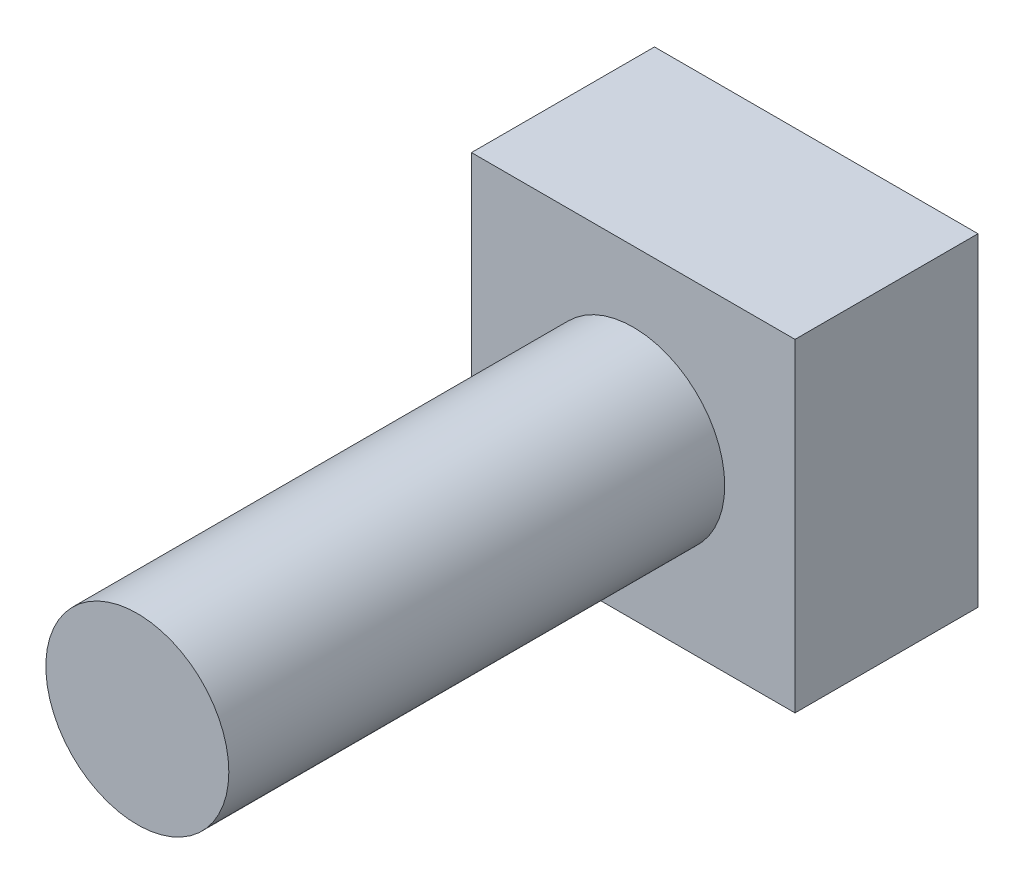
SolidWorks part; units mm, degrees
ref_plane "Front Plane" through (0, 0, 0) normal (0, 0, 1) x (1, 0, 0)
ref_plane "Top Plane" through (0, 0, 0) normal (0, 1, 0) x (1, 0, 0)
ref_plane "Right Plane" through (0, 0, 0) normal (1, 0, 0) x (0, 0, -1)
sketch "Sketch1" plane through (0, 0, 0) normal (0, 0, 1) x (1, 0, 0)
  line L1 (3.0988, -3.0988) -> (-3.0988, -3.0988)
  line L2 (3.0988, -3.0988) -> (3.0988, 3.0988)
  line L3 (3.0988, 3.0988) -> (-3.0988, 3.0988)
  line L4 (-3.0988, -3.0988) -> (-3.0988, 3.0988)
  line L5 (3.0988, -3.0988) -> (-3.0988, 3.0988) construction
  line L6 (3.0988, 3.0988) -> (-3.0988, -3.0988) construction
  point P0 (0, 0)
  dimension "D1" = 6.1976
  dimension "D2" = 6.1976
extrude "Boss-Extrude1" add sketch "Sketch1" against normal blind 3.5052
sketch "Sketch2" plane through (0, 0, 0) normal (0, 0, 1) x (1, 0, 0)
  circle A0 centre (0, 0) radius 1.7526
  dimension "D1" = 3.5052
extrude "Boss-Extrude2" add sketch "Sketch2" along normal blind 9.4996
